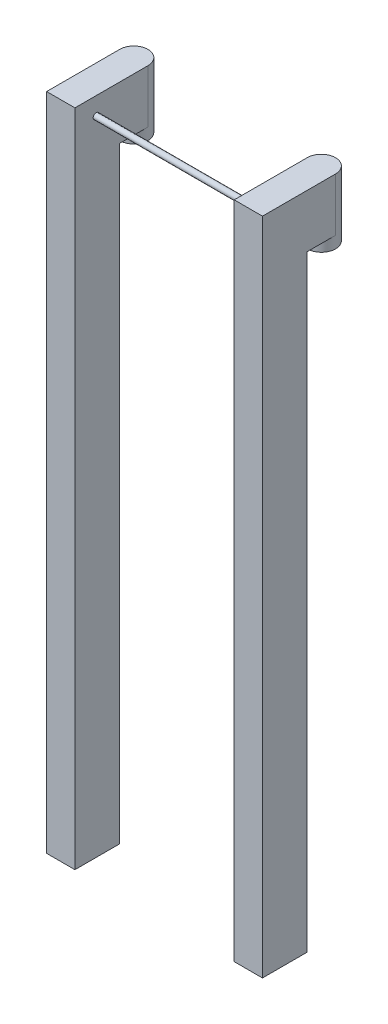
SolidWorks part; units mm, degrees
ref_plane "Front Plane" through (0, 0, 0) normal (0, 0, 1) x (1, 0, 0)
ref_plane "Top Plane" through (0, 0, 0) normal (0, 1, 0) x (1, 0, 0)
ref_plane "Right Plane" through (0, 0, 0) normal (1, 0, 0) x (0, 0, -1)
sketch "Sketch1" plane through (0, 0, 0) normal (0, 1, 0) x (1, 0, 0)
  circle A0 centre (398, 0) radius 31.6967
  circle A1 centre (-398, 0) radius 32.5287
  circle A2 centre (-398, 0) radius 60
  circle A3 centre (398, 0) radius 60
  dimension "D1" = 398
  dimension "D2" = 398
extrude "Boss-Extrude1" add sketch "Sketch1" along normal blind 50
sketch "Sketch2" plane through (0, 50, 0) normal (0, 1, 0) x (1, 0, 0)
  circle A0 centre (398, 0) radius 60
  circle A1 centre (-398, 0) radius 60
extrude "Boss-Extrude2" add sketch "Sketch2" along normal blind 225.5
sketch "Sketch5" plane through (0, 0, 0) normal (0, 0, 1) x (1, 0, 0)
  line L0 (-338, 0) -> (-338, 275.5) construction
  line L1 (-458, 275.5) -> (-338, 275.5)
  line L2 (-458, 275.5) -> (-458, 50)
  line L3 (-458, 50) -> (-338, 50)
  line L4 (-338, 275.5) -> (-338, 50)
  line L5 (458, 0) -> (458, 275.5) construction
  line L6 (338, 275.5) -> (458, 275.5)
  line L7 (338, 275.5) -> (338, 50)
  line L8 (338, 50) -> (458, 50)
  line L9 (458, 275.5) -> (458, 50)
  line L10 (66, 0) -> (-66, 0) construction
  dimension "D1" = 50
  dimension "D2" = 50
extrude "Boss-Extrude3" add sketch "Sketch5" along normal blind 310
sketch "Sketch6" plane through (0, 50, 0) normal (0, -1, 0) x (1, 0, 0)
  line L0 (338, 310) -> (338, 0) construction
  line L1 (458, 310) -> (338, 310)
  line L2 (458, 310) -> (458, 120)
  line L3 (458, 120) -> (338, 120)
  line L4 (338, 310) -> (338, 120)
  line L5 (-458, 310) -> (-458, 0) construction
  line L6 (-338, 310) -> (-458, 310)
  line L7 (-338, 310) -> (-338, 120)
  line L8 (-338, 120) -> (-458, 120)
  line L9 (-458, 310) -> (-458, 120)
  dimension "D1" = 190
  dimension "D2" = 190
extrude "Boss-Extrude4" add sketch "Sketch6" along normal blind 2574.5
sketch "Sketch7" plane through (-338, 0, 0) normal (1, 0, 0) x (0, 0, -1)
  line L1 (-120, 50) -> (-310, 50)
  line L2 (-120, 50) -> (-120, 275.5)
  line L3 (-120, 275.5) -> (-310, 275.5)
  line L4 (-310, 50) -> (-310, 275.5)
extrude "Boss-Extrude5" add sketch "Sketch7" along normal up to surface (676 mm away) up to face at (338, -733, 143.3333)
sketch "Sketch9" plane through (338, 0, 0) normal (-1, 0, 0) x (0, 0, 1)
  line L1 (120, 275.5) -> (310, 275.5)
  line L2 (120, 275.5) -> (120, 50)
  line L3 (120, 50) -> (310, 50)
  line L4 (310, 275.5) -> (310, 50)
  circle A0 centre (220, 200.5) radius 12.5
  dimension "D1" = 75
  dimension "D2" = 100
extrude "Cut-Extrude1" cut sketch "Sketch9" along normal up to surface (676 mm away) up to face at (-338, -1237.25, 215)
